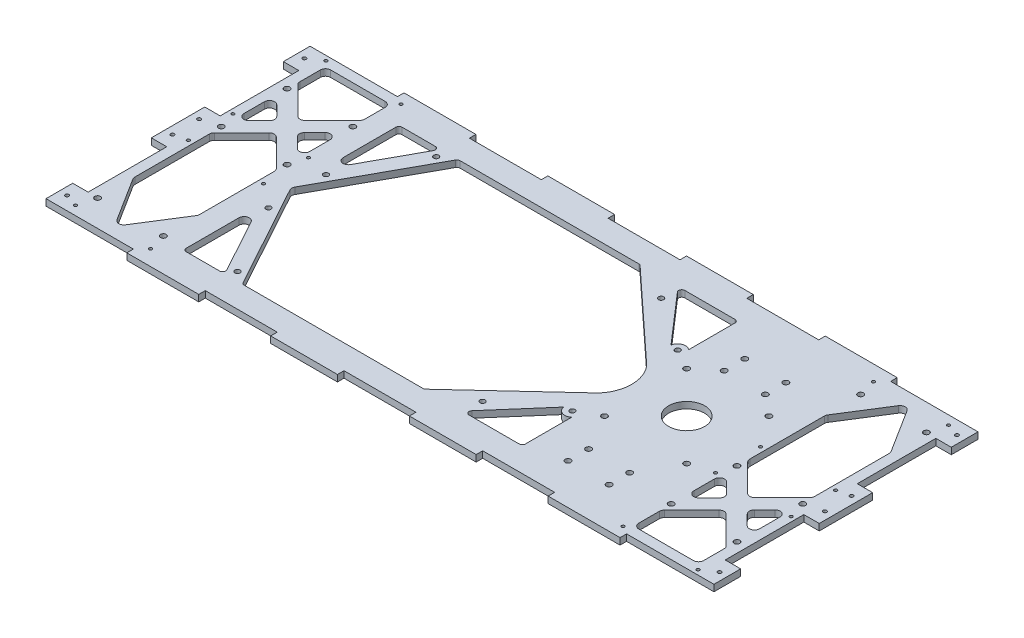
SolidWorks part; units mm, degrees
other "Markup1"
sketch "Sketch10" plane through (-309.99, 6.35, 134.85) normal (-0.3172, 0.7749, 0.5467) x (0.8454, -0.0301, 0.5333)
material "6061-T6 (SS)"
ref_plane "Alzado" through (0, 0, 0) normal (0, 0, 1) x (1, 0, 0)
ref_plane "Planta" through (0, 0, 0) normal (0, 1, 0) x (1, 0, 0)
ref_plane "Vista lateral" through (0, 0, 0) normal (1, 0, 0) x (0, 0, -1)
sketch "Sketch1" plane through (0, 0, 0) normal (0, 1, 0) x (1, 0, 0)
  line L1 (-309.99, -134.85) -> (309.99, -134.85)
  line L2 (-309.99, -134.85) -> (-309.99, 134.85)
  line L3 (-309.99, 134.85) -> (309.99, 134.85)
  line L4 (309.99, -134.85) -> (309.99, 134.85)
  line L5 (-309.99, -134.85) -> (309.99, 134.85) construction
  line L6 (-309.99, 134.85) -> (309.99, -134.85) construction
  point P0 (0, 0)
  dimension "D1" = 619.98
  dimension "D2" = 269.7
extrude "Boss-Extrude1" add sketch "Sketch1" along normal blind 6.35
sketch "Sketch3" plane through (0, 6.35, 0) normal (0, 1, 0) x (1, 0, 0)
  line L0 (309.99, 134.85) -> (-309.99, 134.85) construction
  line L1 (-300.44, 81.52) -> (-236.44, 81.52) construction
  line L2 (-300.44, 81.52) -> (-300.44, 17.52) construction
  line L3 (-300.44, 17.52) -> (-236.44, 17.52) construction
  line L4 (-236.44, 81.52) -> (-236.44, 17.52) construction
  line L5 (-300.44, 81.52) -> (-236.44, 17.52) construction
  line L6 (-300.44, 17.52) -> (-236.44, 81.52) construction
  line L7 (-309.99, 134.85) -> (-309.99, -134.85) construction
  line L8 (-309.99, -134.85) -> (309.99, -134.85) construction
  line L9 (300.44, -81.52) -> (236.44, -81.52) construction
  line L10 (300.44, -81.52) -> (300.44, -17.52) construction
  line L11 (300.44, -17.52) -> (236.44, -17.52) construction
  line L12 (236.44, -81.52) -> (236.44, -17.52) construction
  line L13 (300.44, -81.52) -> (236.44, -17.52) construction
  line L14 (300.44, -17.52) -> (236.44, -81.52) construction
  circle A0 centre (-300.44, -102.85) radius 2.75
  circle A1 centre (-236.44, -102.85) radius 2.75
  circle A2 centre (-300.44, 17.52) radius 2.75
  circle A3 centre (-236.44, 17.52) radius 2.75
  circle A4 centre (-236.44, 81.52) radius 2.75
  circle A5 centre (-300.44, 81.52) radius 2.75
  circle A6 centre (300.44, 102.85) radius 2.75
  circle A7 centre (236.44, 102.85) radius 2.75
  circle A8 centre (300.44, -17.52) radius 2.75
  circle A9 centre (236.44, -17.52) radius 2.75
  circle A10 centre (236.44, -81.52) radius 2.75
  circle A11 centre (300.44, -81.52) radius 2.75
  point P4 (-268.44, 49.52)
  point P25 (268.44, -49.52)
  point P34 (0, 0)
  dimension "D4" = 5.5
  dimension "D1" = 64
  dimension "D2" = 53.33
  dimension "D3" = 9.55
  dimension "D5" = 32
  dimension "D6" = 2
extrude "Cut-Extrude1" cut sketch "Sketch3" against normal blind 6.35
sketch "Sketch2" plane through (0, 6.35, 0) normal (0, 1, 0) x (1, 0, 0)
  line L0 (-309.99, -128.49) -> (309.99, -128.49)
  line L1 (-309.99, 134.85) -> (-309.99, -134.85) construction
  line L2 (309.99, -134.85) -> (309.99, 134.85) construction
  line L3 (-309.99, -134.85) -> (309.99, -134.85) construction
  line L4 (-309.99, 0) -> (309.99, 0) construction
  line L5 (-309.99, 128.49) -> (309.99, 128.49)
  line L6 (-309.99, 118.49) -> (309.99, 118.49)
  line L7 (-309.99, -118.49) -> (309.99, -118.49)
  circle A0 centre (0, 0) radius 5
  point P12 (0, 0)
  dimension "D2" = 10
  dimension "D1" = 6.36
  dimension "D3" = 10
sketch "Sketch6" plane through (0, 6.35, 0) normal (0, 1, 0) x (1, 0, 0)
  line L1 (-299.2185, -69.7126) -> (-272.6685, -111.7887)
  line L2 (-309.99, -118.49) -> (309.99, -118.49) construction
  line L5 (-300.44, 59.4489) -> (-300.44, 39.5911)
  line L6 (-300.44, 81.52) -> (-300.44, 17.52) construction
  line L7 (-291.9045, 36.0555) -> (-281.9755, 45.9845)
  line L8 (-281.9755, 53.0555) -> (-291.9045, 62.9845)
  line L9 (-268.44, 17.52) -> (-268.44, 81.52) construction
  line L10 (-300.44, 17.52) -> (-236.44, 17.52) construction
  line L11 (-254.9045, 53.0555) -> (-244.9755, 62.9845)
  line L12 (-244.9755, 36.0555) -> (-254.9045, 45.9845)
  line L13 (-236.44, 59.4489) -> (-236.44, 39.5911)
  line L14 (-299.99, 113.49) -> (-299.99, 93.5911)
  line L15 (-309.99, 118.49) -> (309.99, 118.49) construction
  line L16 (-298.5255, 90.0555) -> (-271.9755, 63.5055)
  line L17 (-264.9045, 63.5055) -> (-238.3545, 90.0555)
  line L18 (-236.89, 93.5911) -> (-236.89, 113.49)
  line L19 (-241.89, 118.49) -> (-294.99, 118.49)
  line L20 (-309.99, 134.85) -> (-309.99, -134.85) construction
  line L21 (-300.44, 81.52) -> (-236.44, 81.52) construction
  line L24 (-299.99, 5.4489) -> (-299.99, -67.0444)
  line L27 (-236.89, -67.0444) -> (-236.89, 5.4489)
  line L28 (-264.2115, -111.7887) -> (-237.6615, -69.7126)
  line L29 (299.2185, 69.7126) -> (272.6685, 111.7887)
  line L30 (-298.5255, 8.9845) -> (-271.9755, 35.5345)
  line L31 (-264.9045, 35.5345) -> (-238.3545, 8.9845)
  line L32 (300.44, -59.4489) -> (300.44, -39.5911)
  line L33 (291.9045, -36.0555) -> (281.9755, -45.9845)
  line L34 (281.9755, -53.0555) -> (291.9045, -62.9845)
  line L35 (254.9045, -53.0555) -> (244.9755, -62.9845)
  line L36 (244.9755, -36.0555) -> (254.9045, -45.9845)
  line L37 (236.44, -59.4489) -> (236.44, -39.5911)
  line L38 (299.99, -113.49) -> (299.99, -93.5911)
  line L39 (298.5255, -90.0555) -> (271.9755, -63.5055)
  line L40 (264.9045, -63.5055) -> (238.3545, -90.0555)
  line L41 (236.89, -93.5911) -> (236.89, -113.49)
  line L42 (241.89, -118.49) -> (294.99, -118.49)
  line L43 (299.99, -5.4489) -> (299.99, 67.0444)
  line L44 (236.89, 67.0444) -> (236.89, -5.4489)
  line L45 (264.2115, 111.7887) -> (237.6615, 69.7126)
  line L46 (298.5255, -8.9845) -> (271.9755, -35.5345)
  line L47 (264.9045, -35.5345) -> (238.3545, -8.9845)
  line L48 (268.44, -17.52) -> (268.44, -81.52) construction
  arc A0 (-238.3545, 90.0555) -> (-236.89, 93.5911) centre (-241.89, 93.5911) ccw
  arc A1 (-299.99, 93.5911) -> (-298.5255, 90.0555) centre (-294.99, 93.5911) ccw
  arc A2 (-271.9755, 63.5055) -> (-264.9045, 63.5055) centre (-268.44, 67.0411) ccw
  arc A3 (-300.44, 39.5911) -> (-291.9045, 36.0555) centre (-295.44, 39.5911) ccw
  arc A4 (-291.9045, 62.9845) -> (-300.44, 59.4489) centre (-295.44, 59.4489) ccw
  arc A5 (-281.9755, 45.9845) -> (-281.9755, 53.0555) centre (-285.5111, 49.52) ccw
  arc A6 (-254.9045, 53.0555) -> (-254.9045, 45.9845) centre (-251.3689, 49.52) ccw
  arc A7 (-244.9755, 36.0555) -> (-236.44, 39.5911) centre (-241.44, 39.5911) ccw
  arc A8 (-244.9755, 62.9845) -> (-236.44, 59.4489) centre (-241.44, 59.4489) cw
  arc A9 (-236.89, 113.49) -> (-241.89, 118.49) centre (-241.89, 113.49) ccw
  arc A10 (-299.99, 113.49) -> (-294.99, 118.49) centre (-294.99, 113.49) cw
  arc A11 (-272.6685, -111.7887) -> (-264.2115, -111.7887) centre (-268.44, -109.1204) ccw
  arc A12 (-237.6615, -69.7126) -> (-236.89, -67.0444) centre (-241.89, -67.0444) ccw
  arc A13 (-299.99, -67.0444) -> (-299.2185, -69.7126) centre (-294.99, -67.0444) ccw
  arc A14 (-238.3545, 8.9845) -> (-236.89, 5.4489) centre (-241.89, 5.4489) cw
  arc A15 (-298.5255, 8.9845) -> (-299.99, 5.4489) centre (-294.99, 5.4489) ccw
  arc A16 (-271.9755, 35.5345) -> (-264.9045, 35.5345) centre (-268.44, 31.9989) cw
  arc A17 (238.3545, -90.0555) -> (236.89, -93.5911) centre (241.89, -93.5911) ccw
  arc A18 (299.99, -93.5911) -> (298.5255, -90.0555) centre (294.99, -93.5911) ccw
  arc A19 (271.9755, -63.5055) -> (264.9045, -63.5055) centre (268.44, -67.0411) ccw
  arc A20 (300.44, -39.5911) -> (291.9045, -36.0555) centre (295.44, -39.5911) ccw
  arc A21 (291.9045, -62.9845) -> (300.44, -59.4489) centre (295.44, -59.4489) ccw
  arc A22 (281.9755, -45.9845) -> (281.9755, -53.0555) centre (285.5111, -49.52) ccw
  arc A23 (254.9045, -53.0555) -> (254.9045, -45.9845) centre (251.3689, -49.52) ccw
  arc A24 (244.9755, -36.0555) -> (236.44, -39.5911) centre (241.44, -39.5911) ccw
  arc A25 (244.9755, -62.9845) -> (236.44, -59.4489) centre (241.44, -59.4489) cw
  arc A26 (236.89, -113.49) -> (241.89, -118.49) centre (241.89, -113.49) ccw
  arc A27 (299.99, -113.49) -> (294.99, -118.49) centre (294.99, -113.49) cw
  arc A28 (272.6685, 111.7887) -> (264.2115, 111.7887) centre (268.44, 109.1204) ccw
  arc A29 (237.6615, 69.7126) -> (236.89, 67.0444) centre (241.89, 67.0444) ccw
  arc A30 (299.99, 67.0444) -> (299.2185, 69.7126) centre (294.99, 67.0444) ccw
  arc A31 (238.3545, -8.9845) -> (236.89, -5.4489) centre (241.89, -5.4489) cw
  arc A32 (298.5255, -8.9845) -> (299.99, -5.4489) centre (294.99, -5.4489) ccw
  arc A33 (271.9755, -35.5345) -> (264.9045, -35.5345) centre (268.44, -31.9989) cw
  point P37 (-299.99, 91.52)
  point P40 (-268.44, 59.97)
  point P43 (-300.44, 27.52)
  point P46 (-300.44, 71.52)
  point P49 (-278.44, 49.52)
  point P52 (-258.44, 49.52)
  point P55 (-236.44, 27.52)
  point P58 (-236.44, 71.52)
  point P61 (-236.89, 118.49)
  point P64 (-299.99, 118.49)
  point P67 (-268.44, -118.49)
  point P75 (-299.99, -68.49)
  point P78 (-236.89, 7.52)
  point P81 (-299.99, 7.52)
  point P84 (-268.44, 39.07)
  point P137 (0, 0)
  dimension "D5" = 5
  dimension "D8" = 5
  dimension "D1" = 10
  dimension "D2" = 10
  dimension "D3" = 10
  dimension "D4" = 20
  dimension "D6" = 50
  dimension "D7" = 20
  dimension "D9" = 2
extrude "Cut-Extrude2" cut sketch "Sketch6" against normal blind 6.35
sketch "Sketch7" plane through (0, 6.35, 0) normal (0, 1, 0) x (1, 0, 0)
  line L0 (-309.99, 0) -> (309.99, 0) construction
  line L1 (309.99, -134.85) -> (309.99, 134.85) construction
  line L2 (209.99, -40) -> (129.99, -40) construction
  line L3 (209.99, -40) -> (209.99, 40) construction
  line L4 (209.99, 40) -> (129.99, 40) construction
  line L5 (129.99, -40) -> (129.99, 40) construction
  line L6 (209.99, -40) -> (129.99, 40) construction
  line L7 (209.99, 40) -> (129.99, -40) construction
  line L8 (129.99, 0) -> (209.99, 0) construction
  line L9 (149.99, -95.5) -> (189.99, -75.5) construction
  line L10 (149.99, -75.5) -> (189.99, -95.5) construction
  line L11 (149.99, 56.5) -> (189.99, 56.5) construction
  line L12 (149.99, 56.5) -> (149.99, 76.5) construction
  line L13 (149.99, 76.5) -> (189.99, 76.5) construction
  line L14 (189.99, 56.5) -> (189.99, 76.5) construction
  line L15 (149.99, 56.5) -> (189.99, 76.5) construction
  line L16 (149.99, 76.5) -> (189.99, 56.5) construction
  line L17 (189.99, -75.5) -> (189.99, -95.5) construction
  line L18 (149.99, -95.5) -> (189.99, -95.5) construction
  line L19 (149.99, -75.5) -> (149.99, -95.5) construction
  line L20 (149.99, -75.5) -> (189.99, -75.5) construction
  circle A0 centre (169.99, 0) radius 17.5
  circle A1 centre (129.99, 40) radius 2.75
  circle A2 centre (209.99, 40) radius 2.75
  circle A3 centre (209.99, -40) radius 2.75
  circle A4 centre (129.99, -40) radius 2.75
  circle A5 centre (149.99, 76.5) radius 2.75
  circle A6 centre (189.99, 76.5) radius 2.75
  circle A7 centre (189.99, 56.5) radius 2.75
  circle A8 centre (149.99, 56.5) radius 2.75
  circle A9 centre (149.99, -75.5) radius 2.75
  circle A10 centre (189.99, -75.5) radius 2.75
  circle A11 centre (189.99, -95.5) radius 2.75
  circle A12 centre (149.99, -95.5) radius 2.75
  point P10 (169.99, 66.5)
  point P20 (169.99, 0)
  point P37 (169.99, -85.5)
  dimension "D1" = 40
  dimension "D2" = 5.5
  dimension "D5" = 35
  dimension "D6" = 4
  dimension "D10" = 95.5
  dimension "D8" = 76.5
  dimension "D3" = 80
  dimension "D4" = 140
  dimension "D7" = 20
  dimension "D9" = 40
extrude "Cut-Extrude3" cut sketch "Sketch7" against normal blind 6.35
sketch "Sketch8" plane through (0, 6.35, 0) normal (0, 1, 0) x (1, 0, 0)
  line L0 (104.0255, 15) -> (30, 15)
  line L1 (3.6808, 2.4048) -> (-58.5763, 115.8948)
  line L2 (-151.4237, 115.8948) -> (-213.6808, 2.4048)
  line L3 (-147.0399, 118.49) -> (-62.9601, 118.49)
  line L4 (115, -51.2273) -> (115, -113.49)
  line L5 (25, 20) -> (25, 105.1211)
  line L6 (52.0804, -110.2089) -> (106.2271, -47.9462)
  line L7 (-309.99, 118.49) -> (309.99, 118.49) construction
  line L8 (33.7729, 108.4022) -> (107.7984, 23.2811)
  line L9 (-309.99, 0) -> (309.99, 0) construction
  line L10 (0, -118.49) -> (0, 118.49) construction
  line L11 (-309.99, 0) -> (309.99, 0) construction
  line L12 (52.0804, 110.2089) -> (106.2271, 47.9462)
  line L13 (115, 51.2273) -> (115, 113.49)
  line L14 (110, 118.49) -> (55.8533, 118.49)
  line L15 (110, -118.49) -> (55.8533, -118.49)
  line L16 (25, -20) -> (25, -105.1211)
  line L17 (104.0255, -15) -> (30, -15)
  line L18 (33.7729, -108.4022) -> (107.7984, -23.2811)
  line L19 (-151.4237, -115.8948) -> (-213.6808, -2.4048)
  line L20 (-147.0399, -118.49) -> (-62.9601, -118.49)
  line L21 (3.6808, -2.4048) -> (-58.5763, -115.8948)
  line L22 (-34.4455, 118.49) -> (0, 118.49)
  line L23 (5, 113.49) -> (5, 50.6985)
  line L24 (-4.3837, 48.2937) -> (-38.8292, 111.0852)
  line L25 (-105, 118.49) -> (-105, -118.49) construction
  line L26 (-175.5545, 118.49) -> (-210, 118.49)
  line L27 (-205.6163, 48.2937) -> (-171.1708, 111.0852)
  line L28 (-215, 113.49) -> (-215, 50.6985)
  line L29 (-205.6163, -48.2937) -> (-171.1708, -111.0852)
  line L30 (-215, -113.49) -> (-215, -50.6985)
  line L31 (-175.5545, -118.49) -> (-210, -118.49)
  line L32 (5, -113.49) -> (5, -50.6985)
  line L33 (-34.4455, -118.49) -> (0, -118.49)
  line L34 (-4.3837, -48.2937) -> (-38.8292, -111.0852)
  arc A0 (-215, -113.49) -> (-210, -118.49) centre (-210, -113.49) ccw
  arc A1 (-171.1708, -111.0852) -> (-175.5545, -118.49) centre (-175.5545, -113.49) cw
  arc A2 (-205.6163, -48.2937) -> (-215, -50.6985) centre (-210, -50.6985) ccw
  arc A3 (-151.4237, -115.8948) -> (-147.0399, -118.49) centre (-147.0399, -113.49) ccw
  arc A4 (-62.9601, -118.49) -> (-58.5763, -115.8948) centre (-62.9601, -113.49) ccw
  arc A5 (-34.4455, -118.49) -> (-38.8292, -111.0852) centre (-34.4455, -113.49) cw
  arc A6 (5, -113.49) -> (0, -118.49) centre (0, -113.49) cw
  arc A7 (5, -50.6985) -> (-4.3837, -48.2937) centre (0, -50.6985) ccw
  arc A8 (25, -20) -> (30, -15) centre (30, -20) cw
  arc A9 (25, -105.1211) -> (33.7729, -108.4022) centre (30, -105.1211) ccw
  arc A10 (52.0804, -110.2089) -> (55.8533, -118.49) centre (55.8533, -113.49) ccw
  arc A11 (115, -113.49) -> (110, -118.49) centre (110, -113.49) cw
  arc A12 (104.0255, -15) -> (107.7984, -23.2811) centre (104.0255, -20) cw
  arc A13 (115, -51.2273) -> (106.2271, -47.9462) centre (110, -51.2273) ccw
  arc A14 (115, 113.49) -> (110, 118.49) centre (110, 113.49) ccw
  arc A15 (52.0804, 110.2089) -> (55.8533, 118.49) centre (55.8533, 113.49) cw
  arc A16 (106.2271, 47.9462) -> (115, 51.2273) centre (110, 51.2273) ccw
  arc A17 (104.0255, 15) -> (107.7984, 23.2811) centre (104.0255, 20) ccw
  arc A18 (25, 105.1211) -> (33.7729, 108.4022) centre (30, 105.1211) cw
  arc A19 (30, 15) -> (25, 20) centre (30, 20) cw
  arc A20 (5, 50.6985) -> (-4.3837, 48.2937) centre (0, 50.6985) cw
  arc A21 (0, 118.49) -> (5, 113.49) centre (0, 113.49) cw
  arc A22 (-34.4455, 118.49) -> (-38.8292, 111.0852) centre (-34.4455, 113.49) ccw
  arc A23 (-151.4237, 115.8948) -> (-147.0399, 118.49) centre (-147.0399, 113.49) cw
  arc A24 (-58.5763, 115.8948) -> (-62.9601, 118.49) centre (-62.9601, 113.49) ccw
  arc A25 (3.6808, 2.4048) -> (3.6808, -2.4048) centre (-0.7029, 0) cw
  arc A26 (-213.6808, 2.4048) -> (-213.6808, -2.4048) centre (-209.2971, 0) ccw
  arc A27 (-205.6163, 48.2937) -> (-215, 50.6985) centre (-210, 50.6985) cw
  arc A28 (-175.5545, 118.49) -> (-171.1708, 111.0852) centre (-175.5545, 113.49) cw
  arc A29 (-210, 118.49) -> (-215, 113.49) centre (-210, 113.49) ccw
  point P12 (0, 0)
  point P16 (0, 0)
  point P46 (-215, -118.49)
  point P49 (-167.1087, -118.49)
  point P52 (-215, -31.1879)
  point P55 (-150, -118.49)
  point P58 (-60, -118.49)
  point P61 (-42.8913, -118.49)
  point P64 (5, -118.49)
  point P67 (5, -31.1879)
  point P70 (25, -15)
  point P73 (25, -118.49)
  point P76 (44.8788, -118.49)
  point P79 (115, -118.49)
  point P82 (115, -15)
  point P85 (115, -37.8584)
  point P88 (115, 118.49)
  point P91 (44.8788, 118.49)
  point P94 (115, 37.8584)
  point P97 (115, 15)
  point P100 (25, 118.49)
  point P103 (25, 15)
  point P106 (5, 31.1879)
  point P109 (5, 118.49)
  point P112 (-42.8913, 118.49)
  point P115 (-150, 118.49)
  point P118 (-60, 118.49)
  point P121 (5, 0)
  point P124 (-215, 0)
  point P127 (-215, 31.1879)
  point P130 (-167.1087, 118.49)
  point P133 (-215, 118.49)
  dimension "D10" = 5
  dimension "D1" = 15
  dimension "D2" = 90
  dimension "D3" = 50
  dimension "D4" = 15
  dimension "D5" = 90
  dimension "D6" = 20
  dimension "D7" = 60
  dimension "D8" = 20
  dimension "D9" = 15
extrude "Cut-Extrude4" cut sketch "Sketch8" against normal blind 6.35
sketch "Sketch9" plane through (0, 6.35, 0) normal (0, 1, 0) x (1, 0, 0)
  line L0 (-309.99, -134.85) -> (309.99, -134.85) construction
  line L1 (-309.99, -128.49) -> (-239.99, -128.49)
  line L2 (-309.99, -128.49) -> (-309.99, -134.85)
  line L3 (-309.99, -134.85) -> (-239.99, -134.85)
  line L4 (-239.99, -128.49) -> (-239.99, -134.85)
  line L5 (-309.99, -128.49) -> (-239.99, -134.85) construction
  line L6 (-309.99, -134.85) -> (-239.99, -128.49) construction
  line L7 (-309.99, -128.49) -> (309.99, -128.49) construction
  line L8 (-169.99, -128.49) -> (-99.99, -128.49)
  line L9 (-169.99, -128.49) -> (-169.99, -134.85)
  line L10 (-169.99, -134.85) -> (-99.99, -134.85)
  line L11 (-99.99, -128.49) -> (-99.99, -134.85)
  line L12 (-169.99, -128.49) -> (-99.99, -134.85) construction
  line L13 (-169.99, -134.85) -> (-99.99, -128.49) construction
  line L14 (0, 0) -> (0, -134.85) construction
  line L16 (-35, -128.49) -> (35, -128.49)
  line L17 (-35, -128.49) -> (-35, -134.85)
  line L18 (-35, -134.85) -> (35, -134.85)
  line L19 (35, -128.49) -> (35, -134.85)
  line L20 (-35, -128.49) -> (35, -134.85) construction
  line L21 (-35, -134.85) -> (35, -128.49) construction
  line L22 (309.99, -134.85) -> (239.99, -134.85)
  line L23 (309.99, -134.85) -> (309.99, -128.49)
  line L24 (309.99, -128.49) -> (239.99, -128.49)
  line L25 (239.99, -134.85) -> (239.99, -128.49)
  line L26 (309.99, -134.85) -> (239.99, -128.49) construction
  line L27 (309.99, -128.49) -> (239.99, -134.85) construction
  line L28 (169.99, -128.49) -> (99.99, -128.49)
  line L29 (169.99, -128.49) -> (169.99, -134.85)
  line L30 (169.99, -134.85) -> (99.99, -134.85)
  line L31 (99.99, -128.49) -> (99.99, -134.85)
  line L32 (169.99, -128.49) -> (99.99, -134.85) construction
  line L33 (169.99, -134.85) -> (99.99, -128.49) construction
  point P4 (-274.99, -131.67)
  point P12 (-134.99, -131.67)
  point P22 (0, -131.67)
  point P27 (274.99, -131.67)
  point P33 (134.99, -131.67)
  dimension "D1" = 70
  dimension "D2" = 70
  dimension "D3" = 70
  dimension "D4" = 70
  dimension "D5" = 64.99
  dimension "D6" = 70
  dimension "D7" = 70
  dimension "D8" = 70
  dimension "D9" = 64.99
extrude "Cut-Extrude5" cut sketch "Sketch9" against normal blind 6.35
mirror "Mirror1" about plane through (0, 0, 0) normal (0, 0, 1) of "Cut-Extrude5"
sketch "Sketch11" plane through (0, 6.35, 0) normal (0, 1, 0) x (1, 0, 0)
  line L0 (-70.6451, 118.49) -> (25, 118.49)
  line L1 (-62.9601, 118.49) -> (-147.0399, 118.49) construction
  line L2 (25, 118.49) -> (107.7984, 23.2811)
  line L3 (107.7984, -23.2811) -> (25, -118.49)
  line L4 (25, -118.49) -> (-70.6451, -118.49)
  line L5 (-147.0399, -118.49) -> (-62.9601, -118.49) construction
  line L6 (107.7984, 23.2811) -> (33.7729, 108.4022) construction
  line L7 (-34.4455, -118.49) -> (0, -118.49) construction
  line L8 (-70.6451, -118.49) -> (-70.6451, 118.49)
  arc A0 (107.7984, 23.2811) -> (107.7984, -23.2811) centre (81.0277, 0) cw
extrude "Cut-Extrude6" cut sketch "Sketch11" against normal blind 10
sketch "Sketch12" plane through (0, 6.35, 0) normal (0, 1, 0) x (1, 0, 0)
  line L0 (5, -118.49) -> (107.7984, -23.2811)
  line L1 (-147.0399, -118.49) -> (25, -118.49) construction
  line L2 (107.7984, -23.2811) -> (25, -118.49)
  line L3 (25, -118.49) -> (5, -118.49)
  line L4 (0, 0) -> (309.99, 0) construction
  line L5 (309.99, -128.49) -> (309.99, 128.49) construction
  line L6 (107.7984, 23.2811) -> (25, 118.49)
  line L7 (5, 118.49) -> (107.7984, 23.2811)
  line L8 (25, 118.49) -> (5, 118.49)
  dimension "D1" = 20
extrude "Boss-Extrude2" add sketch "Sketch12" against normal up to surface (6.35 mm away) up to face at (-75.1312, 0, 0)
sketch "Sketch13" plane through (0, 6.35, 0) normal (0, 1, 0) x (1, 0, 0)
  line L0 (-169.99, 134.85) -> (-239.99, 134.85) construction
  line L1 (-218, 134.85) -> (118, 134.85)
  line L2 (-218, 134.85) -> (-218, -134.85)
  line L3 (-218, -134.85) -> (118, -134.85)
  line L4 (118, 134.85) -> (118, -134.85)
  line L5 (-218, 134.85) -> (118, -134.85) construction
  line L6 (-218, -134.85) -> (118, 134.85) construction
  line L8 (-50, 134.85) -> (-50, -134.85)
  line L9 (115, 51.2273) -> (115, 113.49) construction
  line L10 (-215, -50.6985) -> (-215, -113.49) construction
  line L11 (35, -134.85) -> (99.99, -134.85) construction
  point P4 (-50, 0)
  dimension "D1" = 3
  dimension "D2" = 3
  dimension "D3" = 168
sketch "Sketch14" plane through (0, 6.35, 0) normal (0, 1, 0) x (1, 0, 0)
  circle A0 centre (110, 51.2273) radius 7.5
  circle A2 centre (110, 51.2273) radius 2.5
  circle A3 centre (110, -51.2273) radius 7.5
  circle A4 centre (110, -51.2273) radius 2.5
  dimension "D1" = 5
  dimension "D2" = 15
  dimension "D3" = 15
  dimension "D4" = 5
extrude "Boss-Extrude3" add sketch "Sketch14" against normal up to surface (6.35 mm away) up to face at (-79.1312, 0, 0)
sketch "Sketch15" plane through (0, 6.35, 0) normal (0, 1, 0) x (1, 0, 0)
  line L0 (0, 0) -> (-309.99, 0) construction
  line L1 (-309.99, -128.49) -> (-324.99, -128.49)
  line L2 (-309.99, -128.49) -> (-309.99, -102.49)
  line L3 (-309.99, -102.49) -> (-324.99, -102.49)
  line L4 (-324.99, -128.49) -> (-324.99, -102.49)
  line L5 (-309.99, -128.49) -> (-324.99, -102.49) construction
  line L6 (-309.99, -102.49) -> (-324.99, -128.49) construction
  line L7 (-309.99, 128.49) -> (-309.99, -128.49) construction
  line L9 (-309.99, 26) -> (-324.99, 26)
  line L10 (-309.99, 26) -> (-309.99, -26)
  line L11 (-309.99, -26) -> (-324.99, -26)
  line L12 (-324.99, 26) -> (-324.99, -26)
  line L13 (-309.99, 26) -> (-324.99, -26) construction
  line L14 (-309.99, -26) -> (-324.99, 26) construction
  line L15 (-309.99, 128.49) -> (-324.99, 128.49)
  line L16 (-309.99, 128.49) -> (-309.99, 102.49)
  line L17 (-309.99, 102.49) -> (-324.99, 102.49)
  line L18 (-324.99, 128.49) -> (-324.99, 102.49)
  line L19 (-309.99, 128.49) -> (-324.99, 102.49) construction
  line L20 (-309.99, 102.49) -> (-324.99, 128.49) construction
  point P4 (-317.49, -115.49)
  point P15 (-317.49, 0)
  point P21 (-317.49, 115.49)
  dimension "D1" = 15
  dimension "D2" = 26
  dimension "D3" = 52
  dimension "D4" = 26
extrude "Boss-Extrude4" add sketch "Sketch15" against normal up to surface (6.35 mm away) contours L12 L11 L10 L9 | L4 L3 L2 L1 | L18 L17 L16 L15 up to face at (91.243, 0, 95.9452)
sketch "Sketch16" plane through (0, 6.35, 0) normal (0, 1, 0) x (1, 0, 0)
  line L0 (-309.99, -128.49) -> (-324.99, -102.49) construction
  line L1 (-324.99, 26) -> (-309.99, 26) construction
  line L2 (-324.99, 26) -> (-324.99, 0) construction
  line L3 (-324.99, 0) -> (-309.99, 0) construction
  line L4 (-309.99, 26) -> (-309.99, 0) construction
  line L5 (-324.99, 26) -> (-309.99, 0) construction
  line L6 (-324.99, 0) -> (-309.99, 26) construction
  line L7 (-324.99, -26) -> (-309.99, -26) construction
  line L8 (-324.99, -26) -> (-324.99, 0) construction
  line L9 (-324.99, 0) -> (-309.99, 0) construction
  line L10 (-309.99, -26) -> (-309.99, 0) construction
  line L11 (-324.99, -26) -> (-309.99, 0) construction
  line L12 (-324.99, 0) -> (-309.99, -26) construction
  circle A0 centre (-317.49, 115.49) radius 1.75
  circle A1 centre (-317.49, 13) radius 1.75
  circle A2 centre (-317.49, -13) radius 1.75
  circle A3 centre (-317.49, -115.49) radius 1.75
  point P7 (-317.49, 13)
  point P16 (-317.49, -13)
  dimension "D1" = 3.5
extrude "Cut-Extrude7" cut sketch "Sketch16" against normal blind 25
mirror "Mirror2" about plane through (0, 0, 0) normal (1, 0, 0) of "Boss-Extrude4", "Cut-Extrude7"
sketch "Sketch18" plane through (0, 6.35, 0) normal (0, 1, 0) x (1, 0, 0)
  line L0 (-218, 134.85) -> (118, -134.85) construction
  line L1 (-218, -134.85) -> (118, 134.85) construction
  line L2 (0, 0) -> (-218, 0) construction
  line L4 (-209, -28) -> (-209, 28) construction
  line L5 (-218, 134.85) -> (-218, -134.85) construction
  line L8 (-151.4237, 115.8948) -> (-213.6808, 2.4048) construction
  line L9 (-213.6808, -2.4048) -> (-151.4237, -115.8948) construction
  line L10 (107.7984, -23.2811) -> (5, -118.49) construction
  line L11 (5, 118.49) -> (107.7984, 23.2811) construction
  circle A0 centre (-170.4967, 96.7201) radius 2.5
  circle A1 centre (-170.4967, -96.7201) radius 2.5
  circle A2 centre (58.2503, -86.8902) radius 2.5
  circle A3 centre (58.2503, 86.8902) radius 2.5
  circle A4 centre (-209, 28) radius 2.5
  circle A5 centre (-209, -28) radius 2.5
  point P24 (-209, 0)
  dimension "D1" = 9
  dimension "D2" = 5
  dimension "D3" = 56
  dimension "D4" = 7.5
  dimension "D5" = 7.5
  dimension "D6" = 13
  dimension "D7" = 13
extrude "Cut-Extrude8" cut sketch "Sketch18" against normal blind 25
sketch "Sketch19" plane through (0, 6.35, 0) normal (0, 1, 0) x (1, 0, 0)
  line L0 (0, -105) -> (0, 105) construction
  line L1 (-215, -105) -> (115, -105)
  line L2 (-215, -50.6985) -> (-215, -113.49) construction
  line L3 (115, -113.49) -> (115, -56.8174) construction
  line L4 (115, -105) -> (115, -121)
  line L5 (115, -121) -> (-215, -121)
  line L6 (-215, -121) -> (-215, -105)
  line L7 (-215, 105) -> (-215, 121)
  line L8 (-215, 113.49) -> (-215, 50.6985) construction
  line L9 (-215, 121) -> (115, 121)
  line L10 (115, 121) -> (115, 105)
  line L11 (115, 56.8174) -> (115, 113.49) construction
  line L12 (115, 105) -> (-215, 105)
  point P4 (0, 0)
  dimension "D1" = 210
  dimension "D2" = 16
  dimension "D3" = 16
extrude "Boss-Extrude5" add sketch "Sketch19" against normal up to surface (6.35 mm away) up to face at (-170.4967, 0, -99.2201)
fillet "Fillet1" radius 3 12 edges at (-174.5089, 3.175, 105) (-157.4002, 3.175, 105) (-215, 3.175, 105) (19.5653, 3.175, 105) (56.6103, 3.175, 105) (115, 3.175, 105) (115, 3.175, -105) (56.6103, 3.175, -105) (19.5653, 3.175, -105) (-157.4002, 3.175, -105) (-174.5089, 3.175, -105) (-215, 3.175, -105)
sketch "Sketch20" plane through (0, 0, 0) normal (0, -1, 0) x (-1, 0, 0)
  circle A0 centre (-304.99, 119.85) radius 1.5
  circle A1 centre (-231.89, 119.85) radius 1.5
  circle A2 centre (-304.99, 10) radius 1.5
  circle A3 centre (-231.89, 10) radius 1.5
  circle A4 centre (-305.44, -33.85) radius 1.5
  circle A5 centre (-231.89, -33.85) radius 1.5
  circle A6 centre (-304.99, -123.85) radius 1.5
  circle A7 centre (-232.0222, -123.9657) radius 1.5
  circle A8 centre (231.89, -119.85) radius 1.5
  circle A9 centre (304.99, -119.85) radius 1.5
  circle A10 centre (304.99, -10) radius 1.5
  circle A11 centre (231.89, -10) radius 1.5
  circle A12 centre (231.89, 33.85) radius 1.5
  circle A13 centre (305.44, 33.85) radius 1.5
  circle A14 centre (304.99, 123.85) radius 1.5
  circle A15 centre (231.89, 123.85) radius 1.5
  dimension "D1" = 3
extrude "Cut-Extrude9" cut sketch "Sketch20" against normal up to surface (6.35 mm away) up to face at (-62.8393, 6.35, 0)
